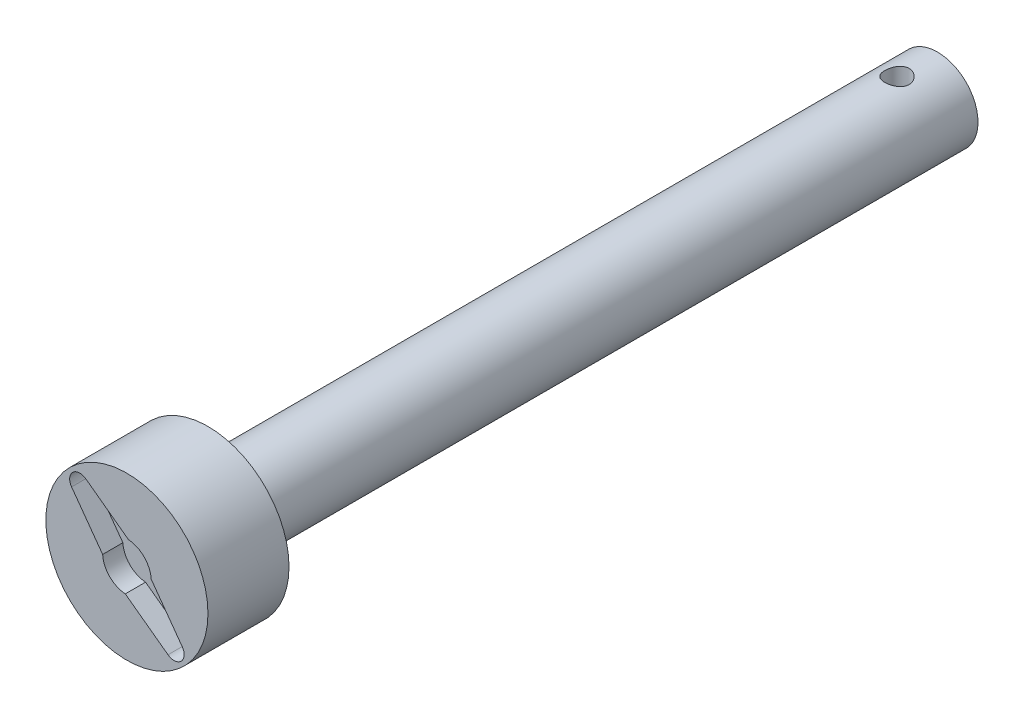
SolidWorks part; units mm, degrees
ref_plane "Front Plane" through (0, 0, 0) normal (0, 0, 1) x (1, 0, 0)
ref_plane "Top Plane" through (0, 0, 0) normal (0, 1, 0) x (1, 0, 0)
ref_plane "Right Plane" through (0, 0, 0) normal (1, 0, 0) x (0, 0, -1)
sketch "Sketch1" plane through (0, 0, 0) normal (0, 0, 1) x (1, 0, 0)
  circle A0 centre (0, 0) radius 10
  dimension "D1" = 20
extrude "Boss-Extrude1" add sketch "Sketch1" along normal blind 200
sketch "Sketch2" plane through (0, 0, 200) normal (0, 0, 1) x (1, 0, 0)
  circle A0 centre (0, 0) radius 20
  dimension "D1" = 40
extrude "Boss-Extrude2" add sketch "Sketch2" against normal blind 20
sketch "Sketch3" plane through (0, 0, 200) normal (0, 0, 1) x (1, 0, 0)
  line L0 (0.3982, 5.9868) -> (-10.144, 13.7262)
  line L1 (-13.6497, 10.2466) -> (-5.9896, -0.3533)
  line L2 (5.9896, 0.3533) -> (13.6497, -10.2466)
  line L3 (10.144, -13.7262) -> (-0.3982, -5.9868)
  arc A0 (-10.144, 13.7262) -> (-13.6497, 10.2466) centre (-11.6234, 11.7109) ccw
  arc A1 (13.6497, -10.2466) -> (10.144, -13.7262) centre (11.6234, -11.7109) cw
  arc A2 (-5.9896, -0.3533) -> (-0.3982, -5.9868) centre (0, 0) ccw
  arc A3 (5.9896, 0.3533) -> (0.3982, 5.9868) centre (0, 0) ccw
  circle A4 centre (11.6234, -11.7109) radius 0.65
  circle A5 centre (9.5101, -9.5817) radius 0.65
  circle A6 centre (-9.5101, 9.5817) radius 0.65
  circle A7 centre (-11.6234, 11.7109) radius 0.65
extrude "Cut-Extrude1" cut sketch "Sketch3" against normal blind 5
sketch "Sketch4" plane through (0, 0, 200) normal (0, 0, 1) x (1, 0, 0)
  circle A0 centre (-9.5101, 9.5817) radius 0.7808
  circle A1 centre (-11.6234, 11.7109) radius 0.65
  circle A2 centre (9.5101, -9.5817) radius 0.65
  circle A3 centre (11.6234, -11.7109) radius 0.65
extrude "Cut-Extrude2" cut sketch "Sketch4" against normal blind 10
sketch "Sketch5" plane through (0, 0, 0) normal (0, 1, 0) x (1, 0, 0)
  circle A0 centre (0, -10) radius 3
  dimension "D1" = 6
  dimension "D2" = 10
extrude "Cut-Extrude3" cut sketch "Sketch5" against normal through all both and the other way through all
